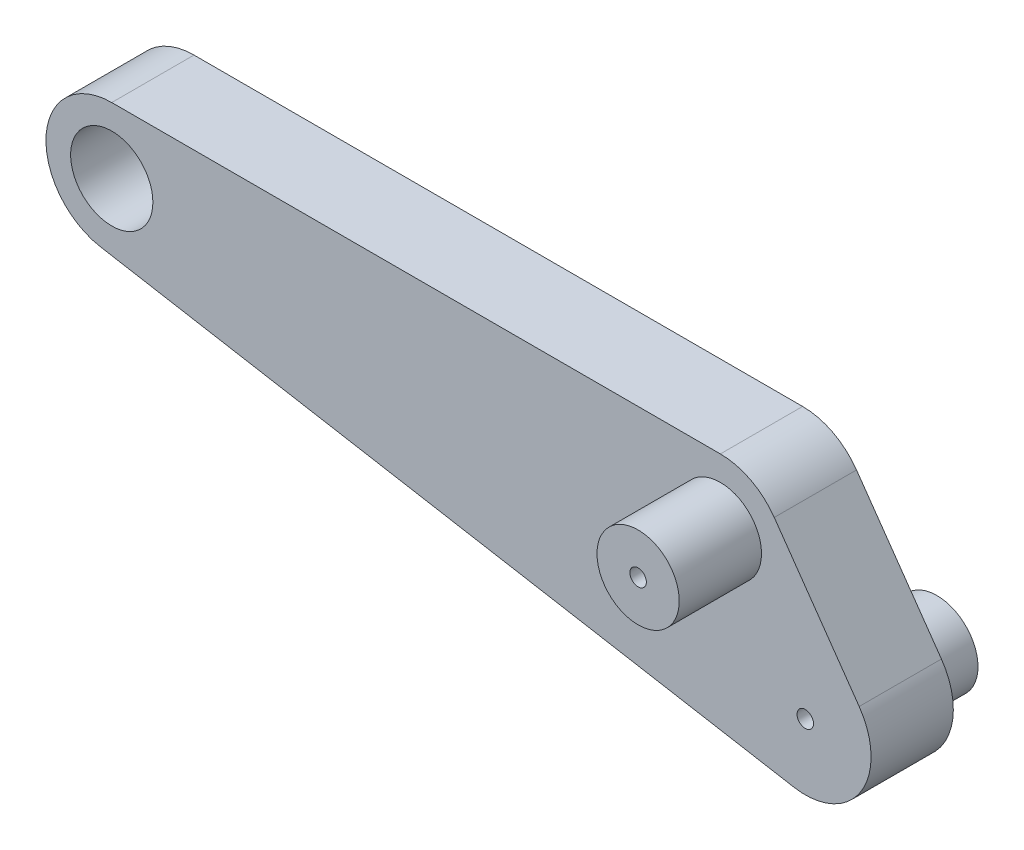
SolidWorks part; units mm, degrees
material "ABS"
ref_plane "Front Plane" through (0, 0, 0) normal (0, 0, 1) x (1, 0, 0)
ref_plane "Top Plane" through (0, 0, 0) normal (0, 1, 0) x (1, 0, 0)
ref_plane "Right Plane" through (0, 0, 0) normal (1, 0, 0) x (0, 0, -1)
sketch "Sketch1" plane through (0, 0, 0) normal (0, 0, 1) x (1, 0, 0)
  line L0 (0, 0) -> (-37, 0)
  line L1 (0, 0) -> (5.1622, -7.3724)
  dimension "D1" = 37
  dimension "D2" = 9
  dimension "D3" = 125
sketch "Sketch2" plane through (0, 0, 0) normal (0, 0, 1) x (1, 0, 0)
  line L0 (-37, 4) -> (0, 4)
  line L1 (3.2766, 2.2943) -> (8.4388, -5.0781)
  line L2 (4.4732, -11.3126) -> (-37.689, -3.9402)
  circle A0 centre (-37, 0) radius 2.5
  arc A1 (-37, 4) -> (-37.689, -3.9402) centre (-37, 0) ccw
  circle A2 centre (0, 0) radius 2.5
  arc A3 (3.2766, 2.2943) -> (0, 4) centre (0, 0) ccw
  circle A4 centre (5.1622, -7.3724) radius 2.5
  arc A5 (4.4732, -11.3126) -> (8.4388, -5.0781) centre (5.1622, -7.3724) ccw
  dimension "D1" = 5
  dimension "D2" = 8
  dimension "D3" = 5
  dimension "D4" = 8
  dimension "D5" = 5
  dimension "D6" = 8
extrude "Boss-Extrude1" add sketch "Sketch2" along normal blind 5
sketch "Sketch3" plane through (0, 0, 5) normal (0, 0, 1) x (1, 0, 0)
  circle A0 centre (5.1622, -7.3724) radius 2.5
  circle A1 centre (5.1622, -7.3724) radius 0.5
  dimension "D1" = 1
  dimension "D2" = 5
extrude "Boss-Extrude2" add sketch "Sketch3" against normal blind 8
sketch "Sketch4" plane through (0, 0, 0) normal (0, 0, -1) x (-1, 0, 0)
  circle A0 centre (0, 0) radius 2.5
  circle A1 centre (0, 0) radius 0.5
  dimension "D1" = 1
  dimension "D2" = 5
extrude "Boss-Extrude3" add sketch "Sketch4" against normal blind 10
